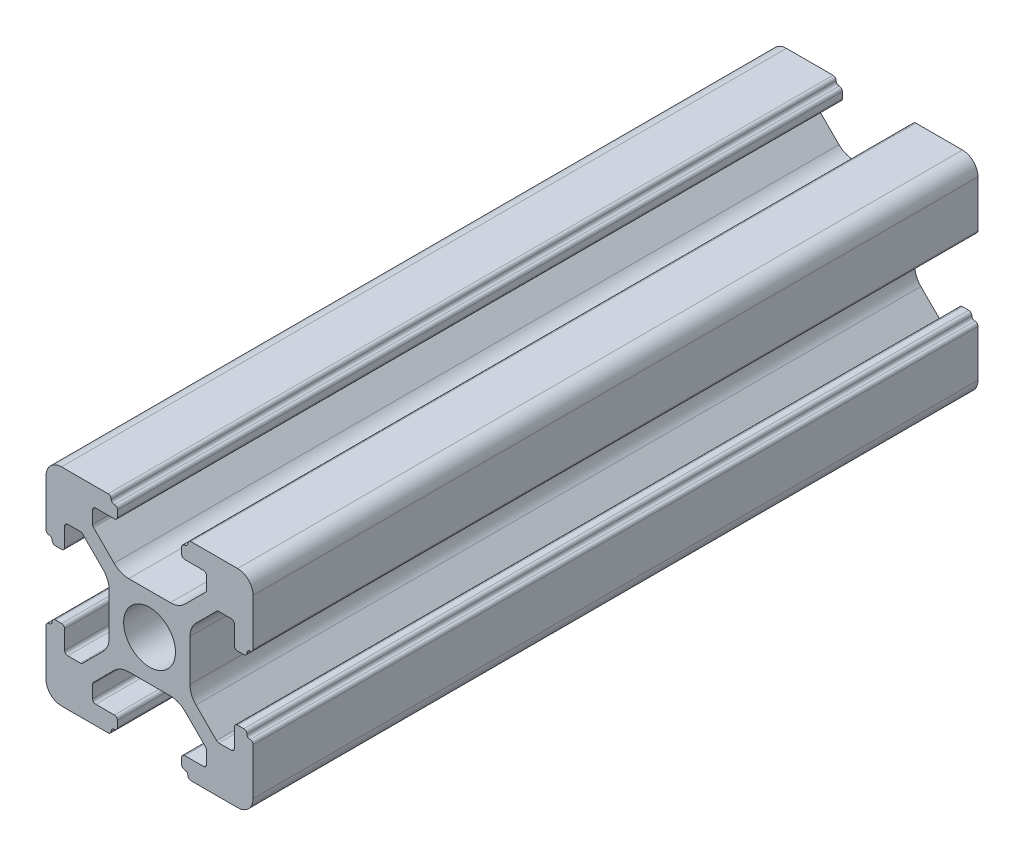
SolidWorks part; units mm, degrees
ref_plane "前视基准面" through (0, 0, 0) normal (0, 0, 1) x (1, 0, 0)
ref_plane "上视基准面" through (0, 0, 0) normal (0, 1, 0) x (1, 0, 0)
ref_plane "右视基准面" through (0, 0, 0) normal (1, 0, 0) x (0, 0, -1)
other "Configuration Table"
sketch "草图1" plane through (0, 0, 0) normal (0, 0, 1) x (1, 0, 0)
  line L0 (-82.8006, 36.1101) -> (-77.8006, 36.1101) construction
  line L1 (-70.3006, 44.6101) -> (-70.3006, 40.1101)
  line L2 (-80.3006, 38.6101) -> (-80.3006, 33.6101) construction
  line L3 (-70.3006, 27.6101) -> (-70.3006, 32.1101)
  line L4 (-71.2006, 33.0101) -> (-71.8006, 33.0101)
  line L5 (-71.2006, 39.2101) -> (-71.8006, 39.2101)
  line L6 (-72.1006, 39.5101) -> (-72.1006, 41.3101)
  line L7 (-72.4006, 41.6101) -> (-73.6157, 41.6101)
  line L8 (-73.8278, 41.5222) -> (-75.8148, 39.5352)
  line L9 (-76.4006, 38.121) -> (-76.4006, 34.0992)
  line L10 (-80.3006, 36.1101) -> (-70.3006, 46.1101) construction
  line L11 (-72.1006, 32.7101) -> (-72.1006, 30.9101)
  line L12 (-72.4006, 30.6101) -> (-73.6157, 30.6101)
  line L13 (-73.8278, 30.698) -> (-75.8148, 32.685)
  line L14 (-74.8885, 42.5829) -> (-76.8755, 40.5959)
  line L15 (-74.8006, 44.0101) -> (-74.8006, 42.795)
  line L16 (-76.9006, 44.3101) -> (-75.1006, 44.3101)
  line L17 (-77.2006, 45.2101) -> (-77.2006, 44.6101)
  line L18 (-71.8006, 46.1101) -> (-76.3006, 46.1101)
  line L19 (-85.7127, 42.5829) -> (-83.7257, 40.5959)
  line L20 (-85.8006, 44.0101) -> (-85.8006, 42.795)
  line L21 (-83.7006, 44.3101) -> (-85.5006, 44.3101)
  line L22 (-78.2897, 40.0101) -> (-82.3115, 40.0101)
  line L23 (-83.4006, 45.2101) -> (-83.4006, 44.6101)
  line L24 (-88.8006, 46.1101) -> (-84.3006, 46.1101)
  line L25 (-90.3006, 46.1101) -> (-80.3006, 36.1101) construction
  line L26 (-90.3006, 44.6101) -> (-90.3006, 40.1101)
  line L27 (-89.4006, 39.2101) -> (-88.8006, 39.2101)
  line L28 (-84.2006, 34.0992) -> (-84.2006, 38.121)
  line L29 (-88.5006, 39.5101) -> (-88.5006, 41.3101)
  line L30 (-88.2006, 41.6101) -> (-86.9855, 41.6101)
  line L31 (-86.7734, 41.5222) -> (-84.7864, 39.5352)
  line L32 (-90.3006, 27.6101) -> (-90.3006, 32.1101)
  line L33 (-89.4006, 33.0101) -> (-88.8006, 33.0101)
  line L34 (-88.5006, 32.7101) -> (-88.5006, 30.9101)
  line L35 (-88.2006, 30.6101) -> (-86.9855, 30.6101)
  line L36 (-86.7734, 30.698) -> (-84.7864, 32.685)
  line L37 (-74.8885, 29.6373) -> (-76.8755, 31.6243)
  line L38 (-74.8006, 28.2101) -> (-74.8006, 29.4252)
  line L39 (-76.9006, 27.9101) -> (-75.1006, 27.9101)
  line L40 (-82.3115, 32.2101) -> (-78.2897, 32.2101)
  line L41 (-85.7127, 29.6373) -> (-83.7257, 31.6243)
  line L42 (-85.8006, 28.2101) -> (-85.8006, 29.4252)
  line L43 (-83.7006, 27.9101) -> (-85.5006, 27.9101)
  line L44 (-83.4006, 27.0101) -> (-83.4006, 27.6101)
  line L45 (-77.2006, 27.0101) -> (-77.2006, 27.6101)
  line L46 (-71.8006, 26.1101) -> (-76.3006, 26.1101)
  line L47 (-88.8006, 26.1101) -> (-84.3006, 26.1101)
  circle A0 centre (-80.3006, 36.1101) radius 2.5
  arc A1 (-75.8148, 39.5352) -> (-76.4006, 38.121) centre (-74.4006, 38.121) ccw
  arc A2 (-70.3006, 40.1101) -> (-70.6006, 39.8101) centre (-70.6006, 40.1101) cw
  arc A3 (-71.2006, 39.2101) -> (-70.9006, 39.5101) centre (-71.2006, 39.5101) ccw
  arc A4 (-71.8006, 39.2101) -> (-72.1006, 39.5101) centre (-71.8006, 39.5101) cw
  arc A5 (-72.1006, 41.3101) -> (-72.4006, 41.6101) centre (-72.4006, 41.3101) ccw
  arc A6 (-73.6157, 41.6101) -> (-73.8278, 41.5222) centre (-73.6157, 41.3101) ccw
  arc A7 (-70.9006, 39.5101) -> (-70.6006, 39.8101) centre (-70.6006, 39.5101) cw
  arc A8 (-70.3006, 32.1101) -> (-70.6006, 32.4101) centre (-70.6006, 32.1101) ccw
  arc A9 (-70.9006, 32.7101) -> (-70.6006, 32.4101) centre (-70.6006, 32.7101) ccw
  arc A10 (-71.2006, 33.0101) -> (-70.9006, 32.7101) centre (-71.2006, 32.7101) cw
  arc A11 (-71.8006, 33.0101) -> (-72.1006, 32.7101) centre (-71.8006, 32.7101) ccw
  arc A12 (-72.1006, 30.9101) -> (-72.4006, 30.6101) centre (-72.4006, 30.9101) cw
  arc A13 (-73.6157, 30.6101) -> (-73.8278, 30.698) centre (-73.6157, 30.9101) cw
  arc A14 (-75.8148, 32.685) -> (-76.4006, 34.0992) centre (-74.4006, 34.0992) cw
  arc A15 (-76.9006, 45.5101) -> (-76.6006, 45.8101) centre (-76.9006, 45.8101) ccw
  arc A16 (-74.8006, 42.795) -> (-74.8885, 42.5829) centre (-75.1006, 42.795) cw
  arc A17 (-75.1006, 44.3101) -> (-74.8006, 44.0101) centre (-75.1006, 44.0101) cw
  arc A18 (-77.2006, 44.6101) -> (-76.9006, 44.3101) centre (-76.9006, 44.6101) ccw
  arc A19 (-77.2006, 45.2101) -> (-76.9006, 45.5101) centre (-76.9006, 45.2101) cw
  arc A20 (-76.3006, 46.1101) -> (-76.6006, 45.8101) centre (-76.3006, 45.8101) ccw
  arc A21 (-83.7257, 40.5959) -> (-82.3115, 40.0101) centre (-82.3115, 42.0101) ccw
  arc A22 (-85.8006, 42.795) -> (-85.7127, 42.5829) centre (-85.5006, 42.795) ccw
  arc A23 (-85.5006, 44.3101) -> (-85.8006, 44.0101) centre (-85.5006, 44.0101) ccw
  arc A24 (-83.4006, 44.6101) -> (-83.7006, 44.3101) centre (-83.7006, 44.6101) cw
  arc A25 (-83.4006, 45.2101) -> (-83.7006, 45.5101) centre (-83.7006, 45.2101) ccw
  arc A26 (-83.7006, 45.5101) -> (-84.0006, 45.8101) centre (-83.7006, 45.8101) cw
  arc A27 (-84.3006, 46.1101) -> (-84.0006, 45.8101) centre (-84.3006, 45.8101) cw
  arc A28 (-76.8755, 40.5959) -> (-78.2897, 40.0101) centre (-78.2897, 42.0101) cw
  arc A29 (-84.7864, 32.685) -> (-84.2006, 34.0992) centre (-86.2006, 34.0992) ccw
  arc A30 (-90.3006, 40.1101) -> (-90.0006, 39.8101) centre (-90.0006, 40.1101) ccw
  arc A31 (-89.7006, 39.5101) -> (-90.0006, 39.8101) centre (-90.0006, 39.5101) ccw
  arc A32 (-89.4006, 39.2101) -> (-89.7006, 39.5101) centre (-89.4006, 39.5101) cw
  arc A33 (-88.8006, 39.2101) -> (-88.5006, 39.5101) centre (-88.8006, 39.5101) ccw
  arc A34 (-88.5006, 41.3101) -> (-88.2006, 41.6101) centre (-88.2006, 41.3101) cw
  arc A35 (-86.9855, 41.6101) -> (-86.7734, 41.5222) centre (-86.9855, 41.3101) cw
  arc A36 (-84.7864, 39.5352) -> (-84.2006, 38.121) centre (-86.2006, 38.121) cw
  arc A37 (-90.3006, 32.1101) -> (-90.0006, 32.4101) centre (-90.0006, 32.1101) cw
  arc A38 (-89.4006, 33.0101) -> (-89.7006, 32.7101) centre (-89.4006, 32.7101) ccw
  arc A39 (-88.8006, 33.0101) -> (-88.5006, 32.7101) centre (-88.8006, 32.7101) cw
  arc A40 (-88.5006, 30.9101) -> (-88.2006, 30.6101) centre (-88.2006, 30.9101) ccw
  arc A41 (-86.9855, 30.6101) -> (-86.7734, 30.698) centre (-86.9855, 30.9101) ccw
  arc A42 (-89.7006, 32.7101) -> (-90.0006, 32.4101) centre (-90.0006, 32.7101) cw
  arc A43 (-76.8755, 31.6243) -> (-78.2897, 32.2101) centre (-78.2897, 30.2101) ccw
  arc A44 (-74.8006, 29.4252) -> (-74.8885, 29.6373) centre (-75.1006, 29.4252) ccw
  arc A45 (-75.1006, 27.9101) -> (-74.8006, 28.2101) centre (-75.1006, 28.2101) ccw
  arc A46 (-77.2006, 27.6101) -> (-76.9006, 27.9101) centre (-76.9006, 27.6101) cw
  arc A47 (-77.2006, 27.0101) -> (-76.9006, 26.7101) centre (-76.9006, 27.0101) ccw
  arc A48 (-76.9006, 26.7101) -> (-76.6006, 26.4101) centre (-76.9006, 26.4101) cw
  arc A49 (-76.3006, 26.1101) -> (-76.6006, 26.4101) centre (-76.3006, 26.4101) cw
  arc A50 (-83.7006, 26.7101) -> (-84.0006, 26.4101) centre (-83.7006, 26.4101) ccw
  arc A51 (-85.8006, 29.4252) -> (-85.7127, 29.6373) centre (-85.5006, 29.4252) cw
  arc A52 (-85.5006, 27.9101) -> (-85.8006, 28.2101) centre (-85.5006, 28.2101) cw
  arc A53 (-83.4006, 27.6101) -> (-83.7006, 27.9101) centre (-83.7006, 27.6101) ccw
  arc A54 (-83.4006, 27.0101) -> (-83.7006, 26.7101) centre (-83.7006, 27.0101) cw
  arc A55 (-84.3006, 26.1101) -> (-84.0006, 26.4101) centre (-84.3006, 26.4101) ccw
  arc A56 (-83.7257, 31.6243) -> (-82.3115, 32.2101) centre (-82.3115, 30.2101) cw
  arc A57 (-90.3006, 27.6101) -> (-88.8006, 26.1101) centre (-88.8006, 27.6101) ccw
  arc A58 (-71.8006, 26.1101) -> (-70.3006, 27.6101) centre (-71.8006, 27.6101) ccw
  arc A59 (-70.3006, 44.6101) -> (-71.8006, 46.1101) centre (-71.8006, 44.6101) ccw
  arc A60 (-90.3006, 44.6101) -> (-88.8006, 46.1101) centre (-88.8006, 44.6101) cw
  point P47 (-76.4006, 36.1101)
  point P86 (-80.3006, 40.0101)
  point P164 (-84.2006, 36.1101)
  point P165 (-80.3006, 32.2101)
  dimension "D1" = 5
extrude "凸台-拉伸1" add sketch "草图1" along normal blind 70
